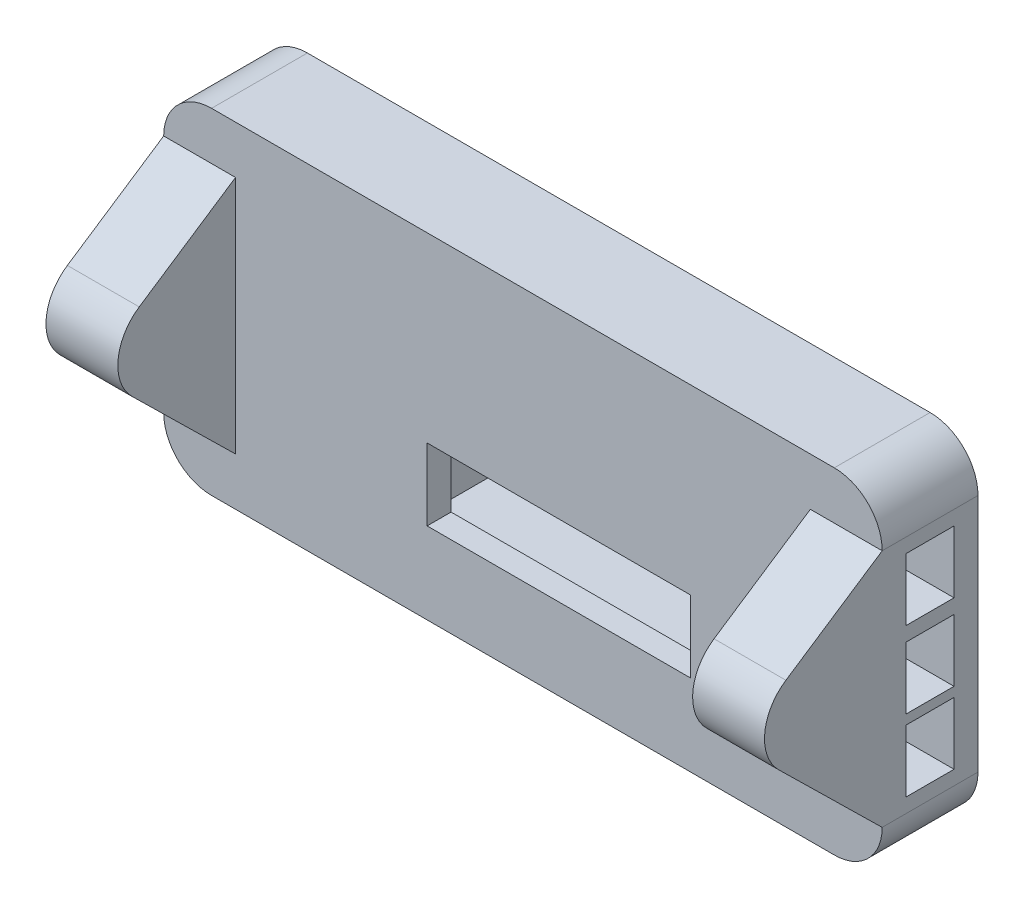
SolidWorks part; units mm, degrees
ref_plane "Front Plane" through (0, 0, 0) normal (0, 0, 1) x (1, 0, 0)
ref_plane "Top Plane" through (0, 0, 0) normal (0, 1, 0) x (1, 0, 0)
ref_plane "Right Plane" through (0, 0, 0) normal (1, 0, 0) x (0, 0, -1)
sketch "Sketch1" plane through (0, 0, 0) normal (0, 0, 1) x (1, 0, 0)
  line L1 (-75.8929, 43.9732) -> (74.1071, 43.9732)
  line L2 (-75.8929, 43.9732) -> (-75.8929, -26.0268)
  line L3 (-75.8929, -26.0268) -> (74.1071, -26.0268)
  line L4 (74.1071, 43.9732) -> (74.1071, -26.0268)
  dimension "D1" = 150
  dimension "D2" = 70
extrude "Boss-Extrude1" add sketch "Sketch1" along normal blind 20 contours L2 L3 L4 L1
fillet "Fillet1" radius 10 4 edges at (-75.8929, -26.0268, 10) (-75.8929, 43.9732, 10) (74.1071, -26.0268, 10) (74.1071, 43.9732, 10)
sketch "Sketch2" plane through (0, 0, 0) normal (0, 0, -1) x (-1, 0, 0)
  line L1 (-55.7359, 24.9301) -> (24.2641, 24.9301)
  line L2 (-55.7359, 24.9301) -> (-55.7359, -10.0699)
  line L3 (-55.7359, -10.0699) -> (24.2641, -10.0699)
  line L4 (24.2641, 24.9301) -> (24.2641, -10.0699)
  dimension "D1" = 80
  dimension "D2" = 35
extrude "Cut-Extrude1" cut sketch "Sketch2" against normal blind 15
sketch "Sketch3" plane through (0, 0, 0) normal (0, 0, -1) x (-1, 0, 0)
  circle A0 centre (40.6152, 4.1726) radius 7
  dimension "D1" = 14
extrude "Cut-Extrude2" cut sketch "Sketch3" against normal blind 15 contours A0
sketch "Sketch4" plane through (74.1071, 0, 0) normal (1, 0, 0) x (0, 0, -1)
  line L0 (0, 33.9732) -> (-20, 33.9732) construction
  line L1 (-15, 30.9732) -> (-5, 30.9732)
  line L2 (-15, 30.9732) -> (-15, 17.9732)
  line L3 (-15, 17.9732) -> (-5, 17.9732)
  line L4 (-5, 30.9732) -> (-5, 17.9732)
  line L5 (-15, 14.9732) -> (-5, 14.9732)
  line L6 (-15, 14.9732) -> (-15, 1.9732)
  line L7 (-15, 1.9732) -> (-5, 1.9732)
  line L8 (-5, 14.9732) -> (-5, 1.9732)
  line L9 (-15, -0.0268) -> (-5, -0.0268)
  line L10 (-15, -0.0268) -> (-15, -13.0268)
  line L11 (-15, -13.0268) -> (-5, -13.0268)
  line L12 (-5, -0.0268) -> (-5, -13.0268)
  line L13 (-20, -16.0268) -> (0, -16.0268) construction
  line L14 (-20, 33.9732) -> (-20, -16.0268) construction
  dimension "D1" = 13
  dimension "D2" = 13
  dimension "D3" = 13
  dimension "D4" = 3
  dimension "D5" = 3
  dimension "D6" = 3
  dimension "D7" = 5
  dimension "D8" = 10
  dimension "D9" = 10
  dimension "D10" = 5
  dimension "D11" = 10
  dimension "D12" = 5
extrude "Cut-Extrude3" cut sketch "Sketch4" against normal blind 15
sketch "Sketch6" plane through (-75.8929, 0, 0) normal (-1, 0, 0) x (0, 0, 1)
  line L0 (20, 33.9732) -> (0, 33.9732) construction
  line L1 (13, 26.9732) -> (17, 26.9732)
  line L2 (13, 26.9732) -> (13, -8.0268)
  line L3 (13, -8.0268) -> (17, -8.0268)
  line L4 (17, 26.9732) -> (17, -8.0268)
  line L5 (20, 33.9732) -> (20, -16.0268) construction
  dimension "D1" = 35
  dimension "D2" = 7
  dimension "D3" = 4
  dimension "D4" = 3
extrude "Cut-Extrude4" cut sketch "Sketch6" against normal blind 25 contours L2 L3 L4 L1
sketch "Sketch7" plane through (0, 0, 20) normal (0, 0, 1) x (1, 0, 0)
  line L0 (-65.8929, -26.0268) -> (64.1071, -26.0268) construction
  line L1 (-20.8929, 5.9732) -> (34.1071, 5.9732)
  line L2 (-20.8929, 5.9732) -> (-20.8929, -9.0268)
  line L3 (-20.8929, -9.0268) -> (34.1071, -9.0268)
  line L4 (34.1071, 5.9732) -> (34.1071, -9.0268)
  line L5 (-75.8929, 33.9732) -> (-75.8929, -16.0268) construction
  dimension "D1" = 17
  dimension "D2" = 55
  dimension "D3" = 110
  dimension "D4" = 15
extrude "Cut-Extrude5" cut sketch "Sketch7" against normal blind 5
sketch "Sketch9" plane through (-75.8929, 0, 0) normal (-1, 0, 0) x (0, 0, 1)
  line L0 (20, 33.9732) -> (50.3812, 13.7952)
  line L1 (50.3812, 13.7952) -> (20, -16.0268)
  line L2 (20, -16.0268) -> (20, 33.9732)
extrude "Boss-Extrude3" add sketch "Sketch9" against normal blind 15
fillet "Fillet2" radius 10 1 edges at (-68.3929, 13.7952, 50.3812)
sketch "Sketch11" plane through (74.1071, 0, 0) normal (1, 0, 0) x (0, 0, -1)
  line L0 (-20, 33.9732) -> (-40.1051, 20.6202)
  line L3 (-41.5776, 5.1537) -> (-20, -16.0268)
  line L4 (-20, -16.0268) -> (-20, 33.9732)
  arc A2 (-40.1051, 20.6202) -> (-41.5776, 5.1537) centre (-34.5725, 12.2901) ccw
extrude "Boss-Extrude4" add sketch "Sketch11" against normal blind 15 contours L0 A2 L3 L4
